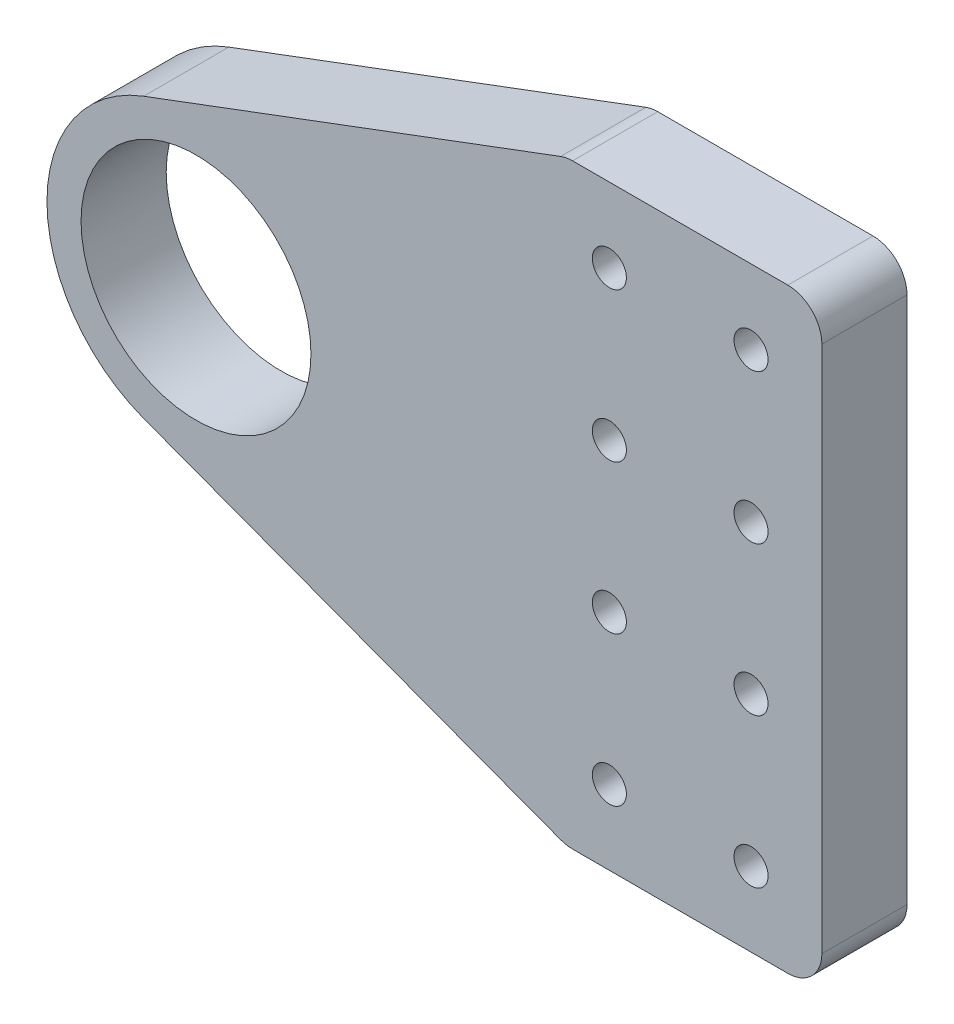
SolidWorks part; units mm, degrees
ref_plane "Front Plane" through (0, 0, 0) normal (0, 0, 1) x (1, 0, 0)
ref_plane "Top Plane" through (0, 0, 0) normal (0, 1, 0) x (1, 0, 0)
ref_plane "Right Plane" through (0, 0, 0) normal (1, 0, 0) x (0, 0, -1)
sketch "Sketch1" plane through (0, 0, 0) normal (0, 0, 1) x (1, 0, 0)
  line L0 (877.2211, -292.1) -> (909.32, -292.1)
  line L1 (914.4, -287.02) -> (914.4, -208.28)
  line L2 (914.4, -225.3961) -> (893.2705, -203.2) construction
  line L3 (893.2705, -203.2) -> (893.2705, -50203.2) construction
  line L4 (876.3, -292.1) -> (876.3, 0) construction
  line L5 (875.4376, -291.7766) -> (813.2522, -268.4603)
  line L6 (838.2, -247.1633) -> (838.2, -50247.1633) construction
  line L7 (821.055, -247.65) -> (50821.055, -247.65) construction
  line L8 (877.2211, -203.2) -> (909.32, -203.2)
  line L9 (875.4376, -203.5234) -> (813.2522, -226.8397)
  line L10 (914.4, -225.425) -> (-49085.6, -225.425) construction
  line L11 (914.4, -269.875) -> (-49085.6, -269.875) construction
  line L12 (893.2705, -203.2) -> (893.2705, -225.425) construction
  line L13 (893.2705, -225.425) -> (914.4, -203.2) construction
  circle A0 centre (821.055, -247.65) radius 17.145
  arc A1 (813.2522, -226.8397) -> (813.2522, -268.4603) centre (821.055, -247.65) ccw
  circle A2 centre (903.8353, -214.298) radius 2.54
  circle A3 centre (882.7058, -214.298) radius 2.54
  circle A4 centre (882.7058, -236.552) radius 2.54
  circle A5 centre (903.8353, -236.552) radius 2.54
  circle A6 centre (882.7058, -258.748) radius 2.54
  circle A7 centre (882.7058, -281.002) radius 2.54
  circle A8 centre (903.8353, -258.748) radius 2.54
  circle A9 centre (903.8353, -281.002) radius 2.54
  arc A10 (877.2211, -203.2) -> (875.4376, -203.5234) centre (877.2211, -208.28) ccw
  arc A11 (877.2211, -292.1) -> (875.4376, -291.7766) centre (877.2211, -287.02) cw
  arc A12 (909.32, -292.1) -> (914.4, -287.02) centre (909.32, -287.02) ccw
  arc A13 (909.32, -203.2) -> (914.4, -208.28) centre (909.32, -208.28) cw
  point P13 (893.2705, -203.2)
  point P29 (0, 0)
  point P31 (903.8353, -214.298)
  point P46 (876.3, -203.2)
  point P49 (876.3, -292.1)
  point P52 (914.4, -292.1)
  dimension "D1" = 34.29
  dimension "D2" = 5.08
  dimension "D5" = 5.08
  dimension "D6" = 5.08
  dimension "D3" = 38.1
  dimension "D4" = 44.45
  dimension "D8" = 22.225
extrude "Boss-Extrude1" add sketch "Sketch1" along normal blind 12.7
